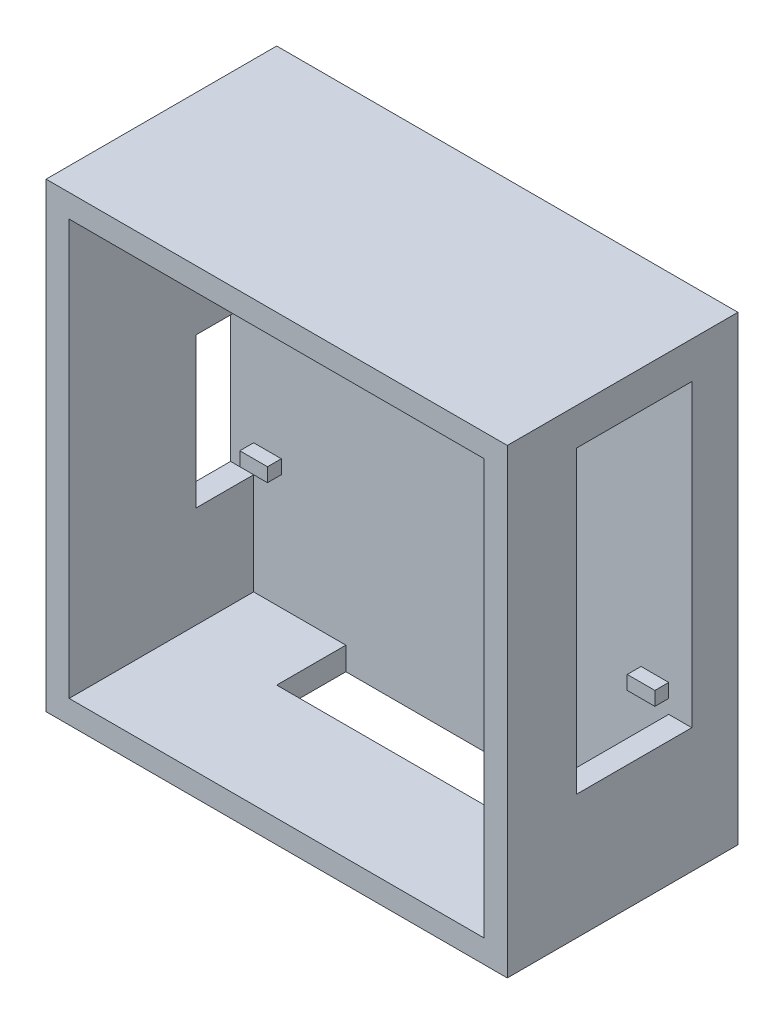
SolidWorks part; units mm, degrees
ref_plane "Front Plane" through (0, 0, 0) normal (0, 0, 1) x (1, 0, 0)
ref_plane "Top Plane" through (0, 0, 0) normal (0, 1, 0) x (1, 0, 0)
ref_plane "Right Plane" through (0, 0, 0) normal (1, 0, 0) x (0, 0, -1)
sketch "Sketch1" plane through (0, 0, 0) normal (0, 0, 1) x (1, 0, 0)
  line L1 (0, 0) -> (100, 0)
  line L2 (0, 0) -> (0, 100)
  line L3 (0, 100) -> (100, 100)
  line L4 (100, 0) -> (100, 100)
  dimension "D1" = 100
  dimension "D2" = 100
extrude "Boss-Extrude1" add sketch "Sketch1" along normal blind 50
shell "Shell1" thickness 10
sketch "Sketch2" plane through (0, 0, 0) normal (0, -1, 0) x (1, 0, 0)
  line L0 (50, 0) -> (50, 50) construction
  line L7 (25, 10) -> (25, 0) construction
  line L8 (0, 0) -> (100, 0) construction
  line L9 (25, 10) -> (25, 25)
  line L10 (25, 10) -> (75, 10)
  line L11 (0, 50) -> (100, 50) construction
  line L12 (25, 25) -> (75, 25)
  line L13 (75, 25) -> (75, 10)
  dimension "D3" = 15
  dimension "D4" = 25
  dimension "D1" = 10
  dimension "D2" = 50
extrude "Cut-Extrude1" cut sketch "Sketch2" against normal blind 10 and the other way through all
sketch "Sketch3" plane through (100, 0, 0) normal (-1, 0, 0) x (0, 0, 1)
  line L0 (22.5, 27) -> (23.4972, 0) construction
  line L1 (35, 27) -> (10, 27)
  line L2 (35, 27) -> (35, 92)
  line L3 (35, 92) -> (10, 92)
  line L4 (10, 27) -> (10, 92)
  line L5 (50, 0) -> (0, 0) construction
  line L6 (10, 59.5) -> (0, 59.5) construction
  line L7 (50, 100) -> (0, 100) construction
  line L9 (0, 100) -> (0, 0) construction
  dimension "D1" = 8
  dimension "D2" = 25
  dimension "D3" = 65
  dimension "D4" = 10
extrude "Cut-Extrude2" cut sketch "Sketch3" along normal blind 10
sketch "Sketch4" plane through (0, 0, 0) normal (1, 0, 0) x (0, 0, -1)
  line L0 (-35, 59.5) -> (-10, 59.5) construction
  line L1 (-35, 27) -> (-35, 92) construction
  line L2 (-10, 92) -> (-10, 27) construction
  line L3 (-22.5, 92) -> (-22.5, 27) construction
  line L4 (-35, 92) -> (-10, 92) construction
  line L5 (-10, 27) -> (-35, 27) construction
  line L7 (-10, 27) -> (-22.5, 27)
  line L8 (-10, 27) -> (-10, 59.5)
  line L9 (-10, 59.5) -> (-22.5, 59.5)
  line L10 (-22.5, 27) -> (-22.5, 59.5)
extrude "Cut-Extrude3" cut sketch "Sketch4" along normal up to surface (10 mm away) up to face at (10, 50, 30)
sketch "Sketch5" plane through (0, 0, 50) normal (0, 0, 1) x (1, 0, 0)
  line L0 (5, 95) -> (5, 5)
  line L1 (100, 100) -> (0, 100) construction
  line L2 (0, 0) -> (100, 0) construction
  line L3 (0, 100) -> (0, 0) construction
  line L4 (5, 95) -> (95, 95)
  line L5 (100, 0) -> (100, 100) construction
  line L6 (95, 95) -> (95, 5)
  line L7 (5, 5) -> (95, 5)
  dimension "D1" = 5
  dimension "D2" = 5
  dimension "D3" = 5
  dimension "D4" = 5
extrude "Cut-Extrude4" cut sketch "Sketch5" against normal up to surface (40 mm away)
sketch "Sketch6" plane through (0, 0, 10) normal (0, 0, 1) x (1, 0, 0)
  line L0 (0, 30) -> (95, 30) construction
  line L1 (95, 95) -> (5, 95) construction
  line L2 (5, 95) -> (5, 30) construction
  line L5 (95, 95) -> (95, 30) construction
  line L7 (5, 30) -> (11, 30)
  line L8 (5, 30) -> (5, 33)
  line L9 (5, 33) -> (11, 33)
  line L10 (11, 30) -> (11, 33)
  line L11 (95, 30) -> (89, 30)
  line L12 (95, 30) -> (95, 33)
  line L13 (95, 33) -> (89, 33)
  line L14 (89, 30) -> (89, 33)
  dimension "D1" = 65
  dimension "D2" = 6
  dimension "D3" = 3
  dimension "D4" = 6
  dimension "D5" = 3
extrude "Boss-Extrude2" add sketch "Sketch6" along normal blind 3
